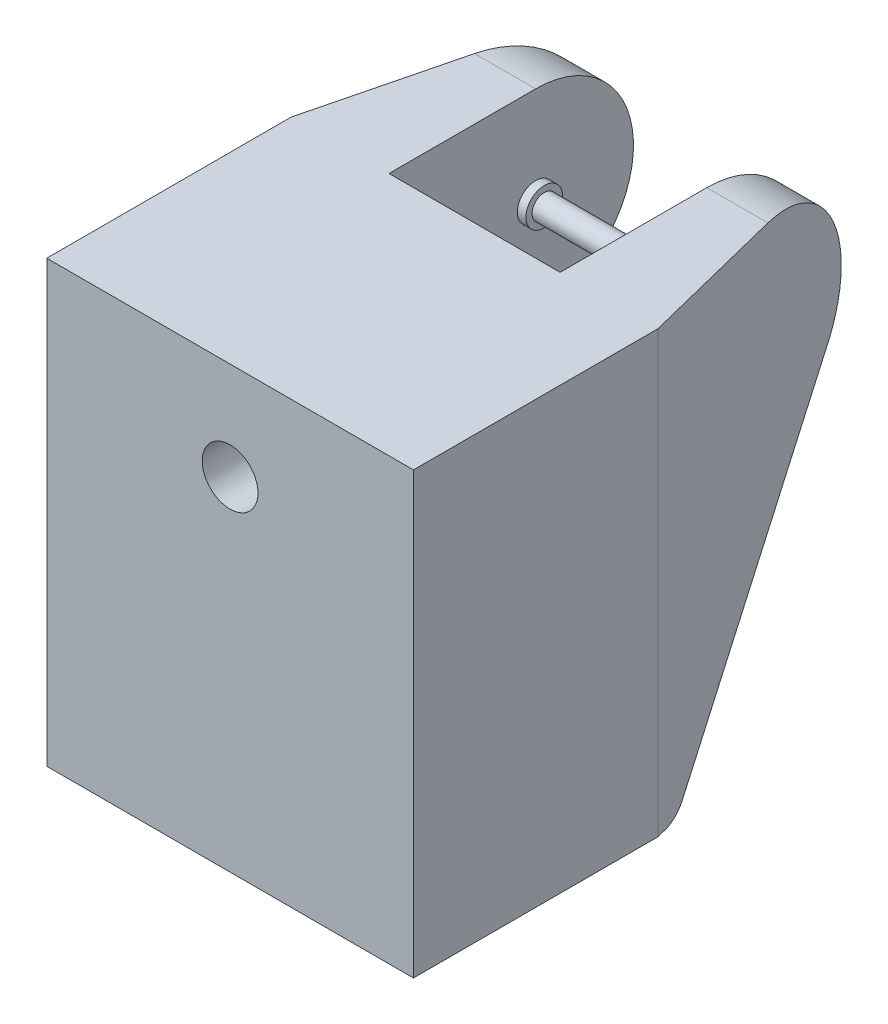
SolidWorks part; units mm, degrees
ref_plane "Front Plane" through (0, 0, 0) normal (0, 0, 1) x (1, 0, 0)
ref_plane "Top Plane" through (0, 0, 0) normal (0, 1, 0) x (1, 0, 0)
ref_plane "Right Plane" through (0, 0, 0) normal (1, 0, 0) x (0, 0, -1)
sketch "Sketch1" plane through (0, 0, 0) normal (0, 0, 1) x (1, 0, 0)
  line L1 (-75, -90) -> (75, -90)
  line L2 (-75, -90) -> (-75, 90)
  line L3 (-75, 90) -> (75, 90)
  line L4 (75, -90) -> (75, 90)
  line L5 (-75, -90) -> (75, 90) construction
  line L6 (-75, 90) -> (75, -90) construction
  dimension "D1" = 150
  dimension "D2" = 180
extrude "Boss-Extrude1" add sketch "Sketch1" along normal blind 110
sketch "Sketch2" plane through (0, 90, 0) normal (0, 1, 0) x (1, 0, 0)
  line L0 (0, 0) -> (0, -10)
  line L1 (75, 0) -> (-75, 0) construction
  line L2 (-35, -10) -> (35, -10)
  line L3 (-35, -10) -> (-35, 0)
  line L4 (-35, 0) -> (35, 0)
  line L5 (35, -10) -> (35, 0)
  line L6 (-35, -10) -> (35, 0) construction
  line L7 (-35, 0) -> (35, -10) construction
  point P3 (0, -5)
  line M3 (75, 0) -> (-75, 0)
  dimension "D1" = 10
  dimension "D2" = 70
extrude "Cut-Extrude1" cut sketch "Sketch2" against normal blind 228 contours L2 L5 L0 M3 | L3 L2 L0 M3
sketch "Sketch3" plane through (-35, 0, 0) normal (1, 0, 0) x (0, 0, -1)
  line L0 (-10, -90) -> (-5.18, -90)
  line L1 (-10, 90) -> (50, 90)
  line L2 (-10, 90) -> (-10, 50)
  line L3 (-10, 50) -> (50, 50)
  line L4 (50, 90) -> (50, 50)
  line L5 (-10, -90) -> (-10, -85.77)
  line L6 (-10, -90) -> (-10, 90) construction
  line L7 (-10, -85.77) -> (2.99, -85.77)
  line L8 (2.99, -85.77) -> (82.6604, 26.9068)
  line L9 (-10, -90) -> (-10, 50)
  circle A0 centre (50, 50) radius 40
  circle A1 centre (50, 50) radius 5
  line M7 (0, -90) -> (0, 90)
  dimension "D3" = 80
  dimension "D7" = 10
  dimension "D1" = 60
  dimension "D2" = 40
  dimension "D4" = 4.82
  dimension "D5" = 4.23
  dimension "D6" = 12.99
extrude "Boss-Extrude2" add sketch "Sketch3" against normal blind 40 contours A0 L1 L3 M7 | A0 L3 L7 L8 M7 | A1 L3 A0 L4 | A1 L4 A0 L3
sketch "Sketch5" plane through (75, 0, 0) normal (1, 0, 0) x (0, 0, -1)
  line L0 (0, 90) -> (50, 90)
  line L1 (0, -85.77) -> (0, 90)
  line L2 (82.6604, 26.9068) -> (2.99, -85.77)
  line L3 (2.99, -85.77) -> (0, -85.77)
  circle A0 centre (50, 50) radius 40
  circle A1 centre (50, 50) radius 5
  line M2 (0, -90) -> (0, 90)
extrude "Boss-Extrude3" add sketch "Sketch5" against normal blind 40 contours A0 L0 L3 L2 M2 | A0 A1
sketch "Sketch6" plane through (75, 0, 0) normal (1, 0, 0) x (0, 0, -1)
  line L2 (2.99, -85.77) -> (0, -90)
  line L3 (0, -90) -> (0, -85.77)
  line L4 (0, -85.77) -> (2.99, -85.77)
extrude "Boss-Extrude5" add sketch "Sketch6" against normal blind 40
sketch "Sketch8" plane through (35, 0, 0) normal (-1, 0, 0) x (0, 0, 1)
  line L0 (10, -90) -> (10, -80)
  line L1 (10, -90) -> (10, 90) construction
  line L2 (10, -80) -> (5.18, -80)
  line L3 (5.18, -80) -> (5.18, -85.77)
  line L5 (5.18, -85.77) -> (-2.99, -85.77)
  line L6 (5.18, -85.77) -> (5.18, -90)
  line L7 (10, -90) -> (0, -90) construction
  line L8 (-2.99, -85.77) -> (0, -90)
  line L9 (0, -90) -> (5.18, -90)
  arc A0 (-2.99, -85.77) -> (5.18, -90) centre (6.1573, -78.1074) ccw
  line M4 (-2.99, -85.77) -> (0, -90)
  line M5 (0, -90) -> (10, -90)
  dimension "D1" = 10
  dimension "D2" = 4.82
  dimension "D3" = 5.77
  dimension "D4" = 8.17
extrude "Cut-Extrude2" cut sketch "Sketch8" against normal blind 40 contours A0 M4 M5
sketch "Sketch9" plane through (-75, 0, 0) normal (-1, 0, 0) x (0, 0, 1)
  line L0 (-2.99, -85.77) -> (0, -90)
  line L1 (0, -90) -> (0, -85.77)
  line L2 (0, -85.77) -> (-2.99, -85.77)
extrude "Boss-Extrude6" add sketch "Sketch9" against normal blind 40
sketch "Sketch10" plane through (-35, 0, 0) normal (1, 0, 0) x (0, 0, -1)
  line L0 (-5.18, -90) -> (0, -90)
  line L1 (0, -90) -> (2.99, -85.77)
  arc A0 (-5.18, -90) -> (2.99, -85.77) centre (-6.1573, -78.1074) ccw
extrude "Cut-Extrude3" cut sketch "Sketch10" against normal blind 40
sketch "Sketch11" plane through (-75, 0, 0) normal (-1, 0, 0) x (0, 0, 1)
  circle A0 centre (-50, 50) radius 5
extrude "Boss-Extrude7" add sketch "Sketch11" against normal blind 30
sketch "Sketch12" plane through (75, 0, 0) normal (1, 0, 0) x (0, 0, -1)
  circle A0 centre (50, 50) radius 5
extrude "Boss-Extrude8" add sketch "Sketch12" against normal blind 30
sketch "Sketch14" plane through (0, 90, 0) normal (0, 1, 0) x (1, 0, 0)
  line L0 (35, -10) -> (75, -10)
  line L1 (75, -110) -> (75, 50) construction
  line L2 (75, -10) -> (75, 0)
  line L3 (75, 0) -> (75, 90)
  line L4 (75, 50) -> (75, 90) construction
  line L5 (75, 90) -> (50, 90)
  line L6 (50, 90) -> (75, -10)
  line L7 (0, -10) -> (0, 0)
  line L8 (-35, -10) -> (35, -10) construction
  line L9 (-50, 90) -> (-75, -10)
  line L10 (-75, 90) -> (-50, 90)
  line L11 (-75, 0) -> (-75, 90)
  line L12 (-75, -10) -> (-75, 0)
  line L13 (-35, -10) -> (-75, -10)
  line M5 (-35, 50) -> (-75, 50)
  line M6 (-75, 50) -> (-75, -110)
  line M8 (75, -110) -> (75, 50)
  line M9 (75, 50) -> (35, 50)
  dimension "D1" = 10
  dimension "D2" = 25
extrude "Cut-Extrude4" cut sketch "Sketch14" against normal blind 187 contours L11 L9 L10 M5 | L9 M5 M6 | L6 M9 M8 | L5 L6 L3 M9
sketch "Sketch16" plane through (-45, 0, 0) normal (1, 0, 0) x (0, 0, -1)
  circle A0 centre (50, 50) radius 5
extrude "Boss-Extrude9" add sketch "Sketch16" along normal up to surface (90 mm away) up to face at (45, 50, -55)
sketch "Sketch17" plane through (-35, 0, 0) normal (1, 0, 0) x (0, 0, -1)
  circle A0 centre (50, 50) radius 5
  circle A1 centre (50, 50) radius 7.5
  dimension "D1" = 15
extrude "Boss-Extrude10" add sketch "Sketch17" along normal blind 3.5
sketch "Sketch18" plane through (35, 0, 0) normal (-1, 0, 0) x (0, 0, 1)
  circle A0 centre (-50, 50) radius 5
  circle A1 centre (-50, 50) radius 7.5
  dimension "D1" = 15
extrude "Boss-Extrude11" add sketch "Sketch18" along normal blind 3.5
sketch "Sketch19" plane through (-31.5, 0, 0) normal (1, 0, 0) x (0, 0, -1)
  circle A0 centre (50, 50) radius 5
sketch "Sketch20" plane through (0, 0, 110) normal (0, 0, 1) x (1, 0, 0)
  line L0 (0, 90) -> (0, 50)
  line L1 (75, 90) -> (-75, 90) construction
  circle A0 centre (0, 50) radius 11.405
  dimension "D2" = 22.81
  dimension "D1" = 40
extrude "Cut-Extrude5" cut sketch "Sketch20" against normal blind 20
